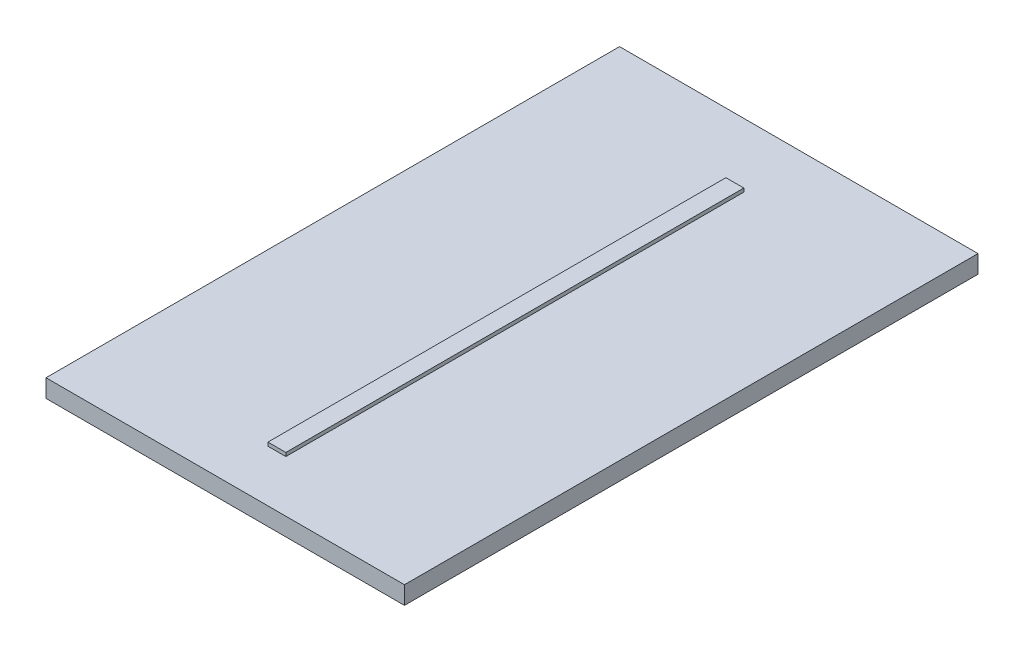
SolidWorks part; units mm, degrees
ref_plane "Front Plane" through (0, 0, 0) normal (0, 0, 1) x (1, 0, 0)
ref_plane "Top Plane" through (0, 0, 0) normal (0, 1, 0) x (1, 0, 0)
ref_plane "Right Plane" through (0, 0, 0) normal (1, 0, 0) x (0, 0, -1)
sketch "Sketch1" plane through (0, 0, 0) normal (0, 1, 0) x (1, 0, 0)
  line L1 (-5, 8) -> (5, 8)
  line L2 (-5, 8) -> (-5, -8)
  line L3 (-5, -8) -> (5, -8)
  line L4 (5, 8) -> (5, -8)
  line L5 (-5, 8) -> (5, -8) construction
  line L6 (-5, -8) -> (5, 8) construction
  point P0 (0, 0)
  dimension "D1" = 10
  dimension "D2" = 16
extrude "Boss-Extrude1" add sketch "Sketch1" along normal blind 0.5
sketch "Sketch3" plane through (0, 0.5, 0) normal (0, 1, 0) x (1, 0, 0)
  line L1 (-0.25, 6.2173) -> (0.25, 6.2173)
  line L2 (-0.25, 6.2173) -> (-0.25, -6.5591)
  line L3 (-0.25, -6.5591) -> (0.25, -6.5591)
  line L4 (0.25, 6.2173) -> (0.25, -6.5591)
  line L5 (-0.25, 6.2173) -> (0.25, -6.5591) construction
  line L6 (-0.25, -6.5591) -> (0.25, 6.2173) construction
  point P0 (0, -0.1709)
  dimension "D1" = 0.5
  dimension "D2" = 12.7764
extrude "Boss-Extrude2" add sketch "Sketch3" along normal blind 0.1
